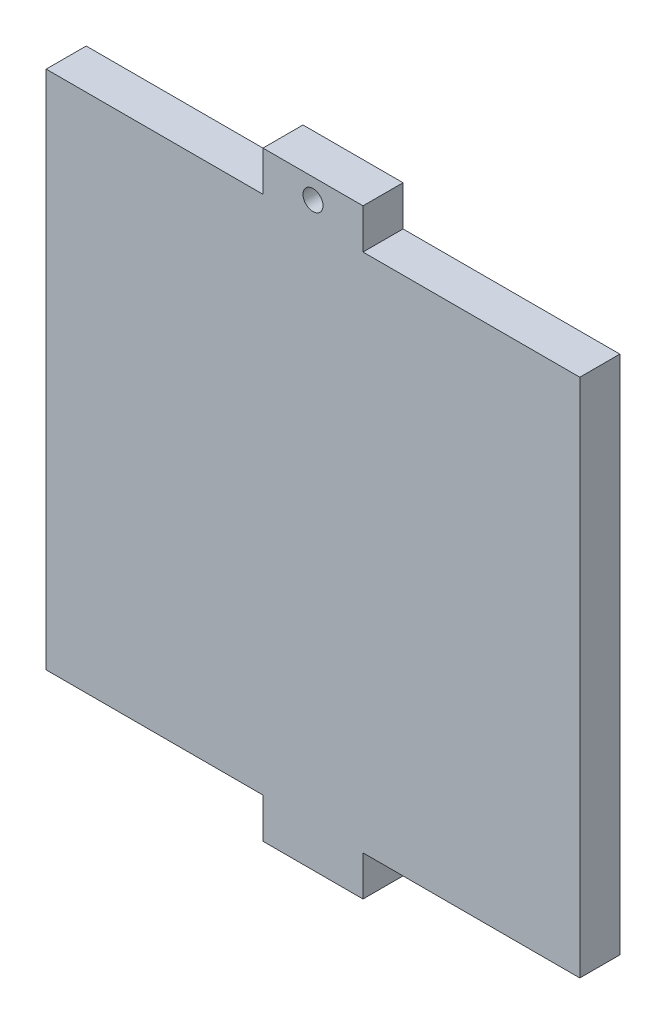
SolidWorks part; units mm, degrees
ref_plane "Plan de face" through (0, 0, 0) normal (0, 0, 1) x (1, 0, 0)
ref_plane "Plan de dessus" through (0, 0, 0) normal (0, 1, 0) x (1, 0, 0)
ref_plane "Plan de droite" through (0, 0, 0) normal (1, 0, 0) x (0, 0, -1)
sketch "Esquisse1" plane through (0, 0, 0) normal (0, 0, 1) x (1, 0, 0)
  line L0 (-47.5, 78) -> (-80, 78)
  line L1 (-80, 39) -> (0, 39) construction
  line L2 (0, 0) -> (0, 78)
  line L3 (0, 78) -> (-32.5, 78)
  line L4 (-80, 0) -> (-80, 78)
  line L5 (-47.5, 0) -> (-80, 0)
  line L6 (-47.5, 78) -> (-47.5, 84)
  line L7 (-47.5, 84) -> (-32.5, 84)
  line L8 (-32.5, 78) -> (-32.5, 84)
  line L9 (0, 0) -> (-32.5, 0)
  line L10 (-32.5, 0) -> (-32.5, -6)
  line L11 (-47.5, -6) -> (-32.5, -6)
  line L12 (-47.5, 0) -> (-47.5, -6)
  dimension "D1" = 78
  dimension "D2" = 80
  dimension "D3" = 32.5
  dimension "D4" = 15
  dimension "D5" = 6
extrude "Boss.-Extru.1" add sketch "Esquisse1" along normal blind 6
sketch "Esquisse2" plane through (0, 0, 0) normal (0, 0, -1) x (-1, 0, 0)
  line L0 (47.5, 84) -> (47.5, 78) construction
  line L1 (32.5, 84) -> (47.5, 84) construction
  circle A0 centre (40, 81) radius 1.5
  point P2 (47.5, 81)
  dimension "D1" = 3
  dimension "D2" = 7.5
  dimension "D3" = 3
extrude "Enlèv. mat.-Extru.1" cut sketch "Esquisse2" against normal blind 6
sketch "Esquisse3" plane through (0, 0, 0) normal (0, 0, -1) x (-1, 0, 0)
  circle A0 centre (40, 81) radius 2.995
  dimension "D1" = 5.99
extrude "Enlèv. mat.-Extru.2" cut sketch "Esquisse3" against normal blind 3
